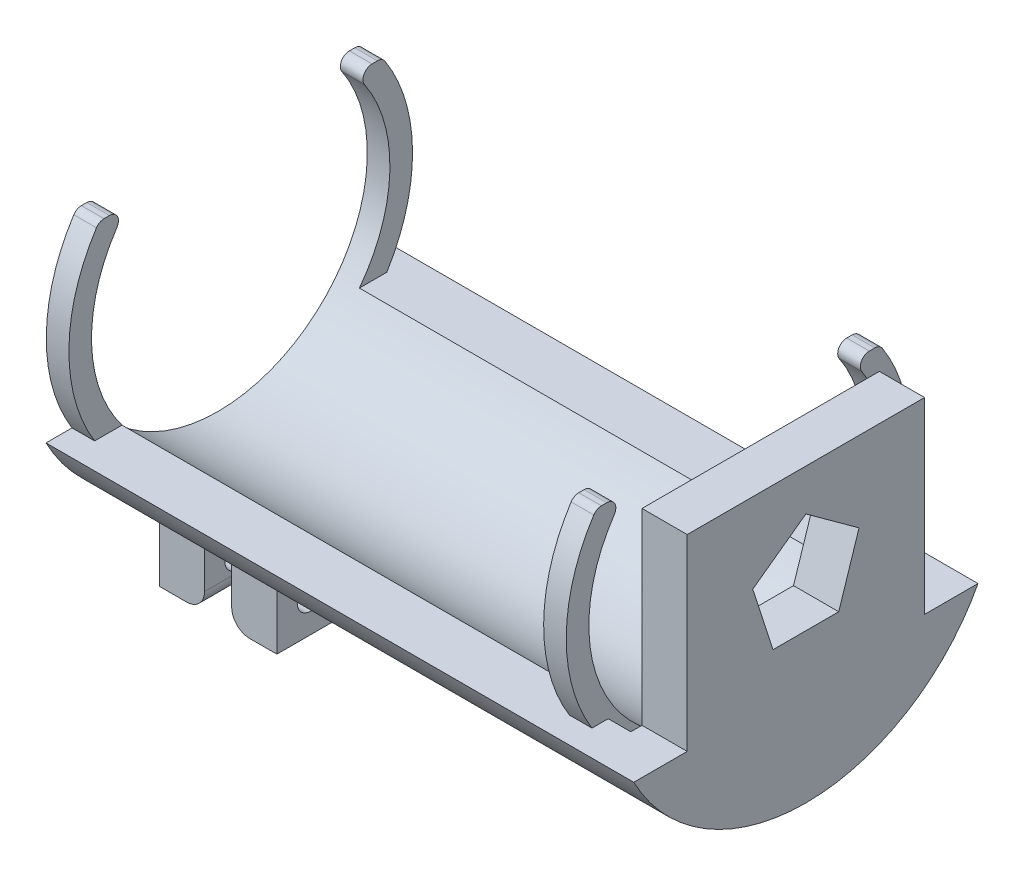
SolidWorks part; units mm, degrees
ref_plane "Front" through (0, 0, 0) normal (0, 0, 1) x (1, 0, 0)
ref_plane "Top" through (0, 0, 0) normal (0, 1, 0) x (1, 0, 0)
ref_plane "Right" through (0, 0, 0) normal (1, 0, 0) x (0, 0, -1)
sketch "Sketch1" plane through (0, 0, 0) normal (1, 0, 0) x (0, 0, -1)
  line L1 (-38.0657, -20) -> (-26.2488, -20)
  line L2 (26.2488, -20) -> (38.0657, -20)
  arc A0 (-26.2488, -20) -> (26.2488, -20) centre (0, 0) ccw
  arc A1 (-38.0657, -20) -> (38.0657, -20) centre (0, 0) ccw
  point P7 (-27.8818, -17.662)
  point P8 (27.8212, -17.6523)
  dimension "D1" = 66
  dimension "D2" = 10
  dimension "D3" = 20
extrude "Boss-Extrude1" add sketch "Sketch1" along normal mid plane 120
sketch "Sketch2" plane through (60, 0, 0) normal (1, 0, 0) x (0, 0, -1)
  line L0 (-31.305, 21.5407) -> (-25, 21.5407)
  line L1 (25, 21.5407) -> (31.305, 21.5407)
  arc A0 (-25, 21.5407) -> (25, 21.5407) centre (0, 0) ccw
  arc A1 (-31.305, 21.5407) -> (31.305, 21.5407) centre (0, 0) ccw
  dimension "D1" = 5
  dimension "D2" = 50
extrude "Boss-Extrude2" add sketch "Sketch2" against normal blind 5 from offset 5 offset against normal yes
sketch "Sketch3" plane through (60, 0, 0) normal (1, 0, 0) x (0, 0, -1)
  line L0 (-26.2488, -20) -> (-26.2488, 21.5407)
  line L1 (-26.2488, 21.5407) -> (26.2488, 21.5407)
  line L2 (26.2488, 21.5407) -> (26.2488, -20)
  line L3 (-25, 21.5407) -> (-31.305, 21.5407) construction
  line L4 (38.0657, -20) -> (26.2488, -20)
  line L7 (-26.2488, -20) -> (-38.0657, -20)
  line L8 (38.0657, -20) -> (26.2488, -20)
  line L11 (-26.2488, -20) -> (-38.0657, -20)
  arc A5 (-26.2488, -20) -> (26.2488, -20) centre (0, 0) ccw
  arc A7 (-38.0657, -20) -> (38.0657, -20) centre (0, 0) ccw
  arc A11 (-38.0657, -20) -> (38.0657, -20) centre (0, 0) ccw
  dimension "D1" = 0
extrude "Boss-Extrude3" add sketch "Sketch3" along normal blind 10
sketch "Sketch4" plane through (0, 0, 0) normal (0, 0, 1) x (1, 0, 0)
  line L0 (-48, -43) -> (-48, -54)
  line L1 (-60, -43) -> (70, -43) construction
  line L2 (-52, -58) -> (-58, -58)
  line L3 (-58, -58) -> (-58, -43)
  line L4 (-45, -43) -> (-45, -58) construction
  line L5 (-58, -43) -> (-48, -43)
  line L6 (-60, -20) -> (-60, -43) construction
  line L7 (-32, -43) -> (-42, -43)
  line L8 (-32, -58) -> (-32, -43)
  line L9 (-38, -58) -> (-32, -58)
  line L10 (-42, -43) -> (-42, -54)
  arc A0 (-38, -58) -> (-42, -54) centre (-38, -54) cw
  arc A1 (-48, -54) -> (-52, -58) centre (-52, -54) cw
  point P16 (-42, -58)
  point P19 (-48, -58)
  dimension "D5" = 4
  dimension "D1" = 15
  dimension "D2" = 3
  dimension "D3" = 10
  dimension "D4" = 15
extrude "Boss-Extrude4" add sketch "Sketch4" along normal mid plane 30 separate body
sketch "Sketch5" plane through (0, -43, 0) normal (0, 1, 0) x (1, 0, 0)
  line L0 (-32, 15) -> (-42, 15) construction
  line L1 (-42, 15) -> (-42, -15) construction
  line L2 (-42, -15) -> (-32, -15) construction
  line L3 (-32, -15) -> (-32, 15) construction
  line L4 (-48, 15) -> (-58, 15) construction
  line L5 (-58, 15) -> (-58, -15) construction
  line L6 (-58, -15) -> (-48, -15) construction
  line L7 (-48, -15) -> (-48, 15) construction
  line L8 (-32, 15) -> (-42, 15)
  line L9 (-42, 15) -> (-42, -15)
  line L10 (-42, -15) -> (-32, -15)
  line L11 (-32, -15) -> (-32, 15)
  line L12 (-48, 15) -> (-58, 15)
  line L13 (-58, 15) -> (-58, -15)
  line L14 (-58, -15) -> (-48, -15)
  line L15 (-48, -15) -> (-48, 15)
extrude "Boss-Extrude6" add sketch "Sketch5" along normal up to surface up to face at (5, -31.5, 0)
sketch "Sketch6" plane through (-58, 0, 0) normal (-1, 0, 0) x (0, 0, 1)
  line L0 (0, -43) -> (0, -58) construction
  line L1 (15, -58) -> (-15, -58) construction
  arc A0 (-15, -40.2989) -> (15, -40.2989) centre (0, 0) ccw construction
  circle A1 centre (-7.5, -50.5) radius 3
  circle A2 centre (7.5, -50.5) radius 3
  point P9 (0, 0)
  point P10 (0, -50.5)
  dimension "D2" = 6
  dimension "D1" = 7.5
extrude "Cut-Extrude1" cut sketch "Sketch6" against normal up to surface (26 mm away) up to face at (-32, -49.8247, 0)
sketch "Sketch7" plane through (60, 0, 0) normal (-1, 0, 0) x (0, 0, 1)
  circle A0 centre (0, 0) radius 35
  dimension "D1" = 70
extrude "Cut-Extrude2" cut sketch "Sketch7" along normal up to surface (5 mm away) up to face at (55, 0.8631, 32.1016)
pattern_linear "LPattern1" count 2 spacing 110 along (-1, 0, 0) of "Boss-Extrude2"
fillet "Fillet1" radius 2 8 edges at (52.5, 21.5407, 25) (52.5, 21.5407, -25) (-57.5, 21.5407, 25) (-57.5, 21.5407, 31.305) (-57.5, 21.5407, -31.305) (-57.5, 21.5407, -25) (52.5, 21.5407, 31.305) (52.5, 21.5407, -31.305)
sketch "Sketch8" plane through (60, 0, 0) normal (-1, 0, 0) x (0, 0, 1)
  line L0 (0, 0) -> (0, 12.3607) construction
  line L1 (0, 12.3607) -> (-11.7557, 3.8197)
  line L2 (-11.7557, 3.8197) -> (-7.2654, -10)
  line L3 (-7.2654, -10) -> (7.2654, -10)
  line L4 (7.2654, -10) -> (11.7557, 3.8197)
  line L5 (11.7557, 3.8197) -> (0, 12.3607)
  circle A0 centre (0, 0) radius 10 construction
  dimension "D1" = 20
extrude "Cut-Extrude3" cut sketch "Sketch8" against normal up to next
